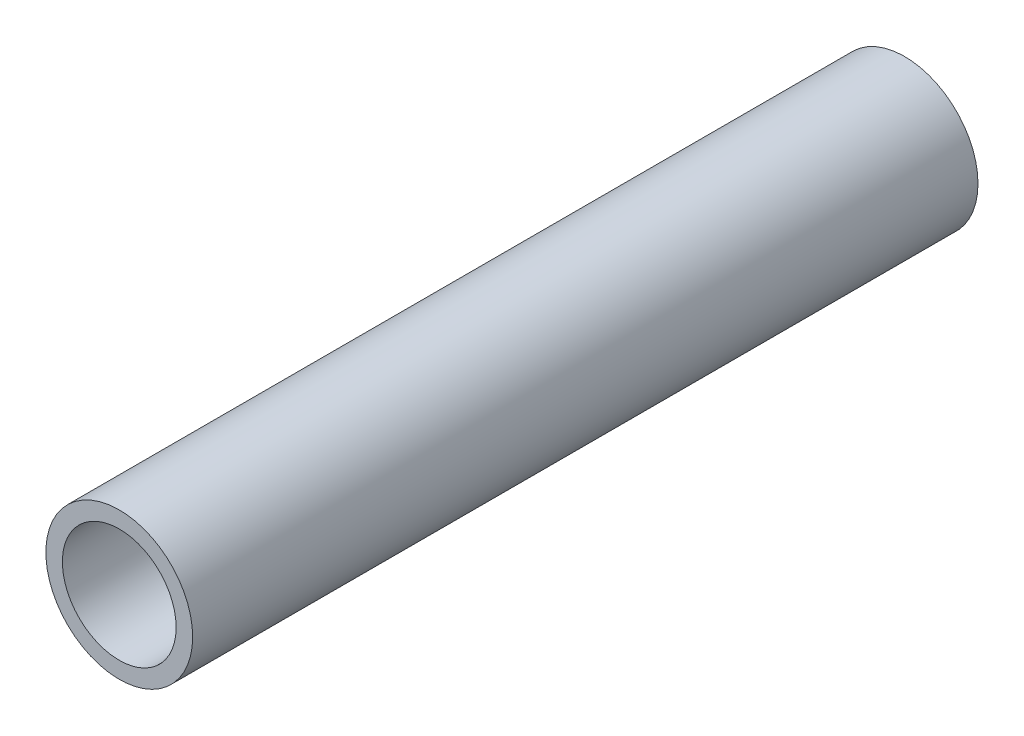
SolidWorks part; units mm, degrees
ref_plane "Спереди" through (0, 0, 0) normal (0, 0, 1) x (1, 0, 0)
ref_plane "Сверху" through (0, 0, 0) normal (0, 1, 0) x (1, 0, 0)
ref_plane "Справа" through (0, 0, 0) normal (1, 0, 0) x (0, 0, -1)
sketch "Эскиз1" plane through (0, 0, 0) normal (0, 0, 1) x (1, 0, 0)
  circle A0 centre (0, 0) radius 1
  circle A1 centre (0, 0) radius 0.775
extrude "Бобышка-Вытянуть1" add sketch "Эскиз1" along normal blind 10.7
